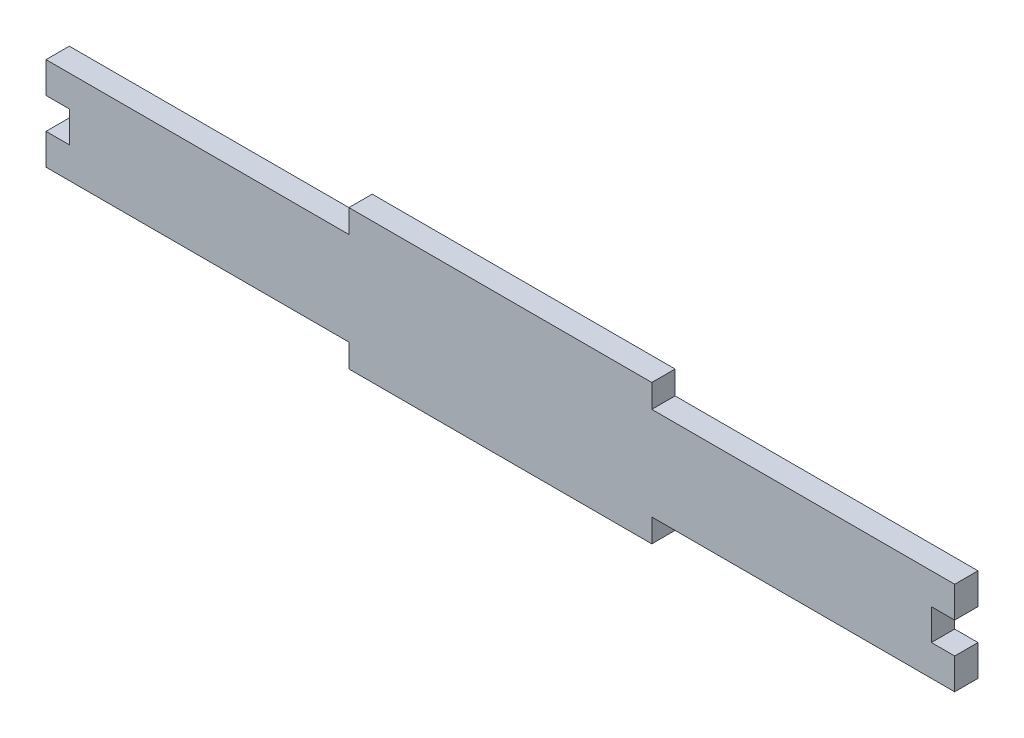
SolidWorks part; units mm, degrees
ref_plane "Front Plane" through (0, 0, 0) normal (0, 0, 1) x (1, 0, 0)
ref_plane "Top Plane" through (0, 0, 0) normal (0, 1, 0) x (1, 0, 0)
ref_plane "Right Plane" through (0, 0, 0) normal (1, 0, 0) x (0, 0, -1)
sketch "Sketch1" plane through (0, 0, 0) normal (0, 0, 1) x (1, 0, 0)
  line L1 (-58.5, -9) -> (58.5, -9) construction
  line L2 (-58.5, -9) -> (-58.5, 9) construction
  line L3 (-58.5, 9) -> (58.5, 9) construction
  line L4 (58.5, -9) -> (58.5, 9) construction
  line L5 (-58.5, -9) -> (58.5, 9) construction
  line L6 (-58.5, 9) -> (58.5, -9) construction
  line L11 (-46.5202, -7.157) -> (46.1062, 7.0933) construction
  line L12 (-46.4777, 5.9587) -> (46.4777, -5.9587) construction
  line L14 (-19.5, -9) -> (19.5, -9)
  line L18 (58.5, -2) -> (55.5, -2)
  line L19 (55.5, -2) -> (55.5, 2)
  line L20 (55.5, 2) -> (58.5, 2)
  line L24 (19.5, 9) -> (-19.5, 9)
  line L28 (-58.5, 2) -> (-55.5, 2)
  line L29 (-55.5, 2) -> (-55.5, -2)
  line L30 (-55.5, -2) -> (-58.5, -2)
  line L32 (-19.5, -9) -> (-19.5, -6)
  line L33 (-19.5, -6) -> (-58.5, -6)
  line L34 (-19.5, 9) -> (-19.5, 6)
  line L35 (-19.5, 6) -> (-58.5, 6)
  line L36 (-58.5, 6) -> (-58.5, 2)
  line L37 (-58.5, -2) -> (-58.5, -6)
  line L38 (19.5, 9) -> (19.5, 6)
  line L39 (19.5, 6) -> (58.5, 6)
  line L40 (58.5, 6) -> (58.5, 2)
  line L41 (58.5, -2) -> (58.5, -6)
  line L42 (58.5, -6) -> (19.5, -6)
  line L43 (19.5, -6) -> (19.5, -9)
  point P0 (0, 0)
  point P6 (0, 0)
  dimension "D1" = 117
  dimension "D2" = 18
  dimension "D3" = 3
extrude "Boss-Extrude1" add sketch "Sketch1" along normal blind 3
